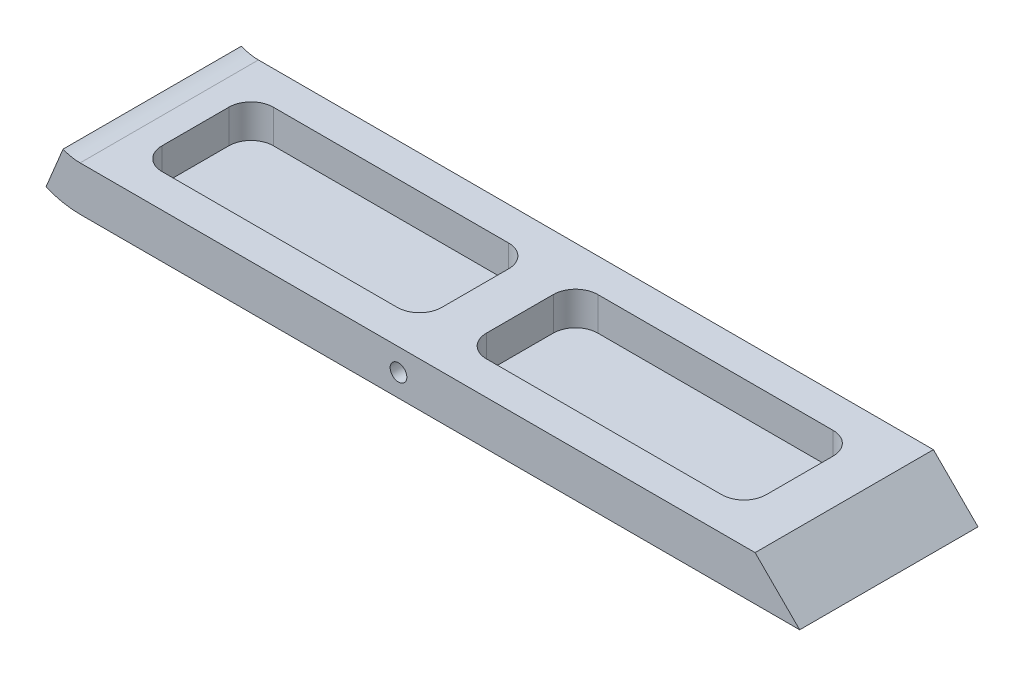
SolidWorks part; units mm, degrees
material "6061 Alloy"
ref_plane "Front Plane" through (0, 0, 0) normal (0, 0, 1) x (1, 0, 0)
ref_plane "Top Plane" through (0, 0, 0) normal (0, 1, 0) x (1, 0, 0)
ref_plane "Right Plane" through (0, 0, 0) normal (1, 0, 0) x (0, 0, -1)
sketch "Sketch1" plane through (0, 0, 0) normal (0, 0, 1) x (1, 0, 0)
  line L0 (0, 0) -> (215.5261, 0)
  line L1 (215.5261, 0) -> (202.8261, 12.7)
  line L2 (202.8261, 12.7) -> (5.2605, 12.7)
  line L3 (5.2605, 12.7) -> (0, 0)
  dimension "D1" = 215.5261
  dimension "D2" = 12.7
  dimension "D3" = 67.5
  dimension "D4" = 45
extrude "Extrude1" add sketch "Sketch1" along normal blind 50.8
sketch "Sketch2" plane through (0, 12.7, 0) normal (0, 1, 0) x (-1, 0, 0)
  line L0 (-202.8261, 50.8) -> (-202.8261, 0) construction
  line L1 (-183.7761, 41.275) -> (-116.7433, 41.275)
  line L2 (-190.1261, 34.925) -> (-190.1261, 15.875)
  line L3 (-183.7761, 9.525) -> (-116.7433, 9.525)
  line L4 (-110.3933, 34.925) -> (-110.3933, 15.875)
  line L5 (-91.3433, 9.525) -> (-24.3105, 9.525)
  line L6 (-97.6933, 15.875) -> (-97.6933, 34.925)
  line L7 (-91.3433, 41.275) -> (-24.3105, 41.275)
  line L8 (-17.9605, 15.875) -> (-17.9605, 34.925)
  line L9 (-5.2605, 50.8) -> (-5.2605, 0) construction
  line L10 (-202.8261, 50.8) -> (-5.2605, 50.8) construction
  arc A0 (-183.7761, 41.275) -> (-190.1261, 34.925) centre (-183.7761, 34.925) ccw
  arc A1 (-116.7433, 41.275) -> (-110.3933, 34.925) centre (-116.7433, 34.925) cw
  arc A2 (-116.7433, 9.525) -> (-110.3933, 15.875) centre (-116.7433, 15.875) ccw
  arc A3 (-190.1261, 15.875) -> (-183.7761, 9.525) centre (-183.7761, 15.875) ccw
  arc A4 (-97.6933, 34.925) -> (-91.3433, 41.275) centre (-91.3433, 34.925) cw
  arc A5 (-91.3433, 9.525) -> (-97.6933, 15.875) centre (-91.3433, 15.875) cw
  arc A6 (-24.3105, 9.525) -> (-17.9605, 15.875) centre (-24.3105, 15.875) ccw
  arc A7 (-24.3105, 41.275) -> (-17.9605, 34.925) centre (-24.3105, 34.925) cw
  point P16 (-110.3933, 41.275)
  point P19 (-110.3933, 9.525)
  point P24 (-97.6933, 41.275)
  point P27 (-97.6933, 9.525)
  dimension "D5" = 6.35
  dimension "D1" = 12.7
  dimension "D2" = 12.7
  dimension "D3" = 12.7
  dimension "D4" = 31.75
  dimension "D6" = 9.525
extrude "Cut-Extrude1" cut sketch "Sketch2" against normal blind 9.525
sketch "Sketch3" plane through (0, 0, 50.8) normal (0, 0, 1) x (1, 0, 0)
  line L0 (202.8261, 12.7) -> (5.2605, 12.7) construction
  circle A0 centre (101.2261, 6.35) radius 2.3813
  dimension "D3" = 4.7625
  dimension "D1" = 114.3
  dimension "D2" = 6.35
extrude "Cut-Extrude2" cut sketch "Sketch3" against normal blind 15.875
sketch "Sketch4" plane through (0, 0, 0) normal (0, 0, -1) x (-1, 0, 0)
  circle A0 centre (-101.2261, 6.35) radius 2.3813
  circle A1 centre (-101.2261, 6.35) radius 2.3813 construction
  dimension "D1" = 4.7625
extrude "Cut-Extrude3" cut sketch "Sketch4" against normal blind 15.875
sketch "Sketch5" plane through (0, 0, 50.8) normal (0, 0, 1) x (1, 0, 0)
  line L0 (0, 0) -> (215.5261, 0) construction
  line L1 (5.2605, 12.7) -> (0, 0) construction
  line L2 (0.8009, 1.9335) -> (0, 0)
  line L3 (0, 0) -> (10.521, 0)
  arc A0 (10.521, 0) -> (0.8009, 1.9335) centre (10.521, 25.4) cw
  dimension "D1" = 25.4
extrude "Cut-Extrude4" cut sketch "Sketch5" against normal through all
sketch "Sketch6" plane through (0, 0, 50.8) normal (0, 0, 1) x (1, 0, 0)
  line L0 (202.8261, 12.7) -> (5.2605, 12.7) construction
  line L1 (5.6609, 13.6667) -> (5.2605, 12.7)
  line L2 (5.2605, 12.7) -> (10.521, 12.7)
  line L3 (5.2605, 12.7) -> (0.8009, 1.9335) construction
  arc A0 (10.521, 12.7) -> (5.6609, 13.6667) centre (10.521, 25.4) cw
  arc A1 (0.8009, 1.9335) -> (10.521, 0) centre (10.521, 25.4) ccw construction
extrude "Extrude2" add sketch "Sketch6" against normal up to surface (50.8 mm away) up to face at (98.8449, 6.35, 0)
